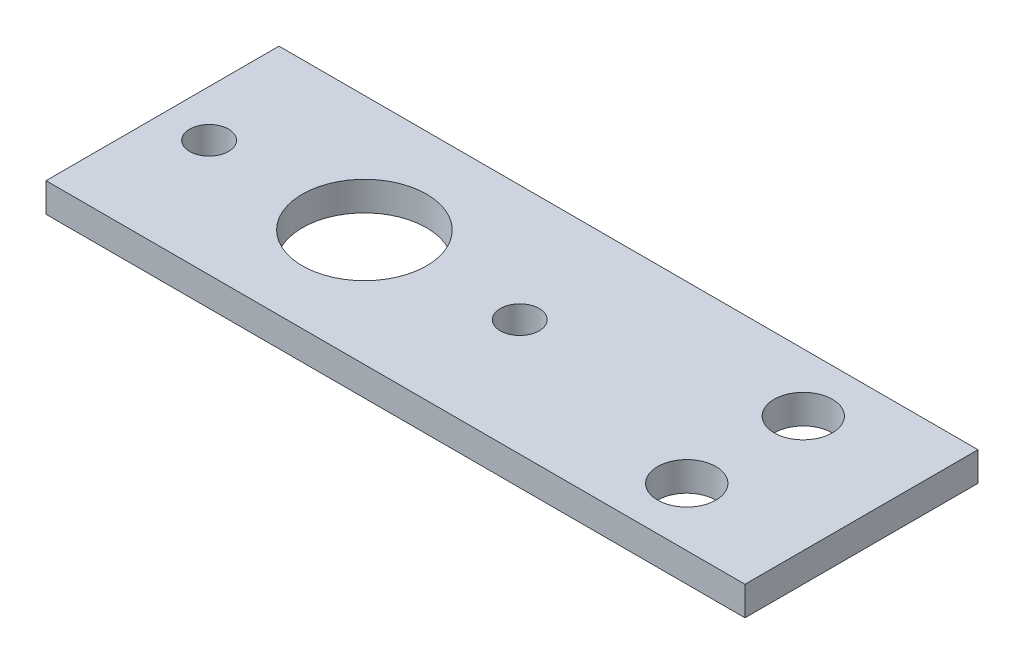
SolidWorks part; units mm, degrees
ref_plane "Front Plane" through (0, 0, 0) normal (0, 0, 1) x (1, 0, 0)
ref_plane "Top Plane" through (0, 0, 0) normal (0, 1, 0) x (1, 0, 0)
ref_plane "Right Plane" through (0, 0, 0) normal (1, 0, 0) x (0, 0, -1)
sketch "Sketch3" plane through (0, 0, 0) normal (0, 1, 0) x (1, 0, 0)
  line L0 (-114.3, 36.8038) -> (-114.3, -48.401) construction
  line L1 (-114.3, -19.05) -> (0, -19.05)
  line L2 (-114.3, -19.05) -> (-114.3, 19.05)
  line L3 (-114.3, 19.05) -> (0, 19.05)
  line L5 (0, 19.05) -> (0, -19.05) construction
  line L6 (-114.3, 0) -> (228.6, 0) construction
  line L7 (-114.3, 36.8038) -> (-48.26, 36.8038) construction
  line L8 (-48.26, 36.8038) -> (-48.26, -48.4673) construction
  line L9 (-81.28, 36.8038) -> (-81.28, -48.4673) construction
  line L10 (0, 19.05) -> (0, -19.05)
  line L11 (-37.0949, 0) -> (-37.0949, 19.05) construction
  circle A0 centre (-106.68, 0) radius 3.175
  circle A1 centre (-81.28, 0) radius 10.16
  circle A2 centre (-55.88, 0) radius 3.175
  circle A4 centre (-19.05, 9.525) radius 4.7625
  circle A5 centre (-19.05, -9.525) radius 4.7625
  point P0 (0, 0)
  dimension "D4" = 20.32
  dimension "D6" = 6.35
  dimension "D2" = 19.05
  dimension "D11" = 9.525
  dimension "D1" = 114.3
  dimension "D3" = 50.8
  dimension "D5" = 25.4
  dimension "D7" = 66.04
  dimension "D8" = 33.02
  dimension "D9" = 19.05
  dimension "D10" = 38.1
extrude "Boss-Extrude1" add sketch "Sketch3" along normal blind 4.7625
